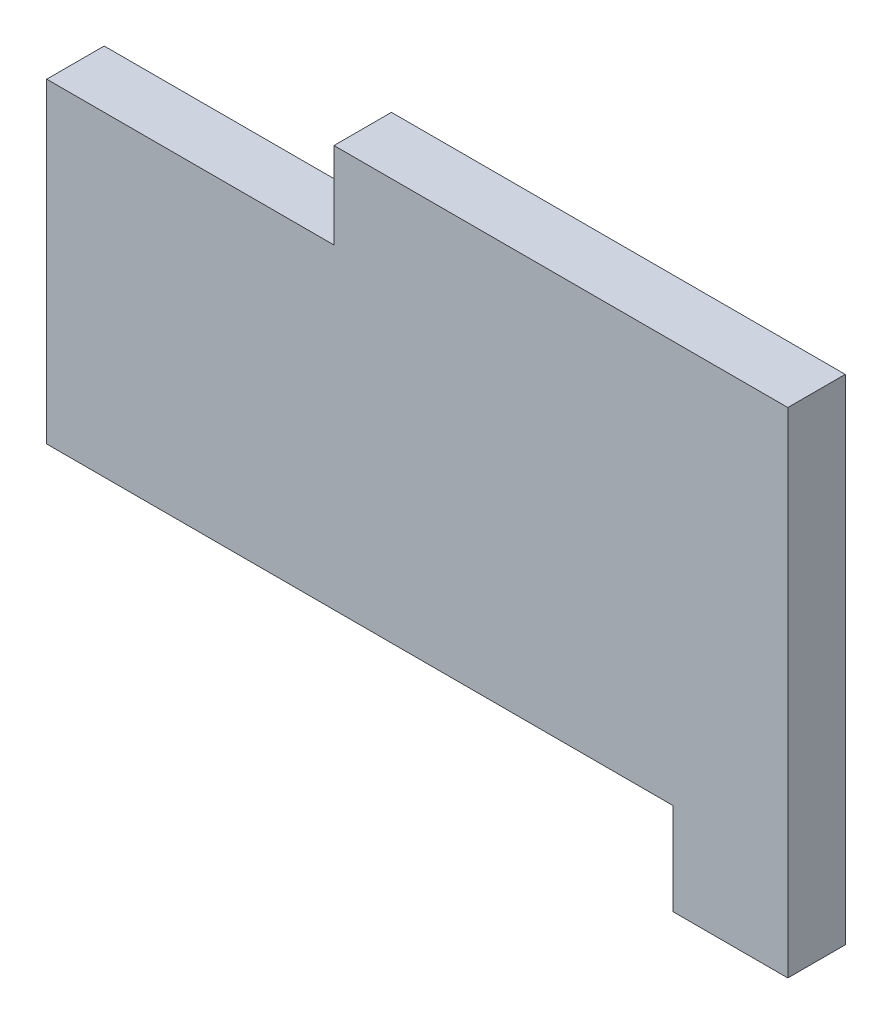
SolidWorks part; units mm, degrees
ref_plane "Front Plane" through (0, 0, 0) normal (0, 0, 1) x (1, 0, 0)
ref_plane "Top Plane" through (0, 0, 0) normal (0, 1, 0) x (1, 0, 0)
ref_plane "Right Plane" through (0, 0, 0) normal (1, 0, 0) x (0, 0, -1)
sketch "Sketch1" plane through (0, 0, 0) normal (0, 0, 1) x (1, 0, 0)
  line L0 (-16.1636, 8.7284) -> (-16.1636, -5.2416)
  line L5 (-16.1636, -5.2416) -> (11.5224, -5.2416)
  line L6 (11.5224, -5.2416) -> (11.5224, -9.3056)
  line L7 (11.5224, -9.3056) -> (16.6024, -9.3056)
  line L8 (16.6024, -9.3056) -> (16.6024, 12.5384)
  line L9 (16.6024, 12.5384) -> (-3.4636, 12.5384)
  line L10 (-3.4636, 12.5384) -> (-3.4636, 8.7284)
  line L11 (-3.4636, 8.7284) -> (-16.1636, 8.7284)
  dimension "D1" = 5.08
  dimension "D2" = 27.686
  dimension "D3" = 13.97
  dimension "D4" = 12.7
  dimension "D5" = 3.81
  dimension "D6" = 21.844
extrude "Boss-Extrude1" add sketch "Sketch1" along normal blind 2.54
